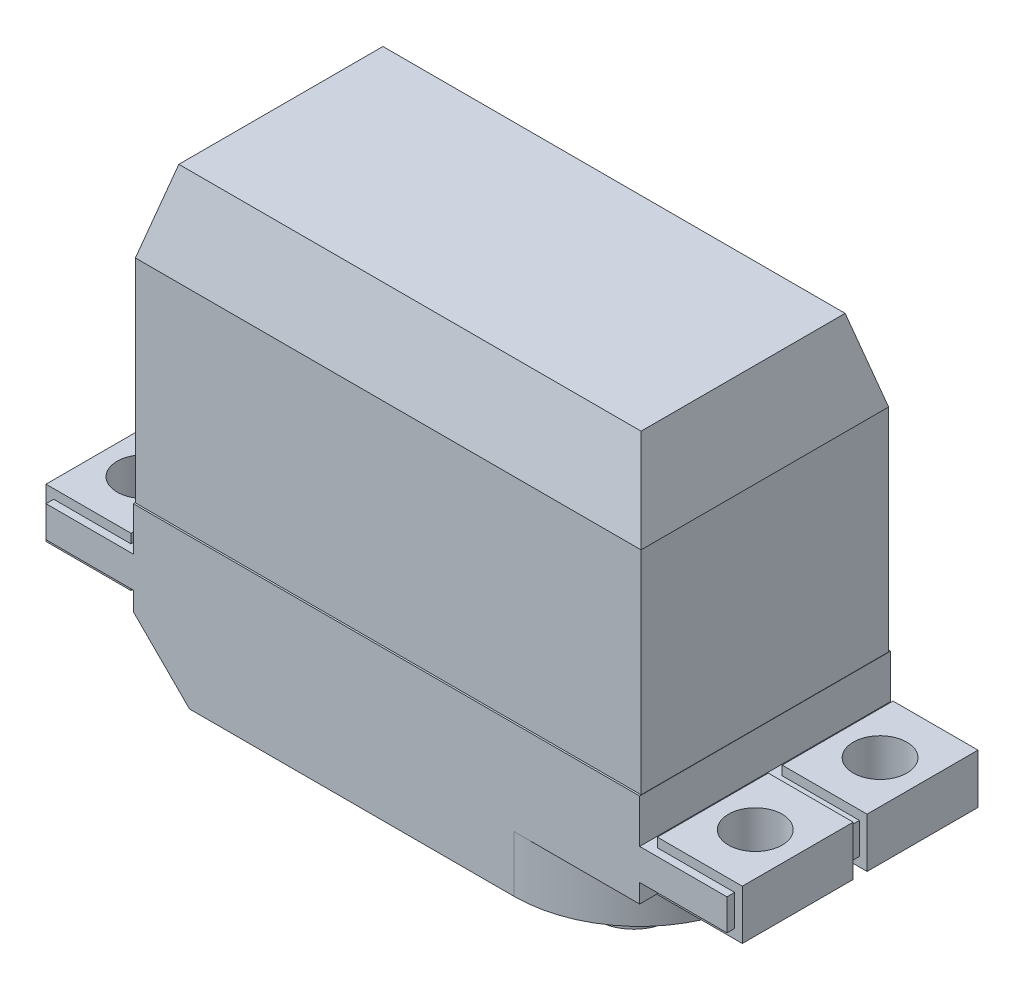
SolidWorks part; units mm, degrees
ref_plane "Piano frontale" through (0, 0, 0) normal (0, 0, 1) x (1, 0, 0)
ref_plane "Piano superiore" through (0, 0, 0) normal (0, 1, 0) x (1, 0, 0)
ref_plane "Piano destro" through (0, 0, 0) normal (1, 0, 0) x (0, 0, -1)
sketch "Schizzo1" plane through (0, 0, 0) normal (0, 1, 0) x (1, 0, 0)
  line L1 (-20.265, -9.92) -> (20.265, -9.92)
  line L2 (-20.265, -9.92) -> (-20.265, 9.92)
  line L3 (-20.265, 9.92) -> (20.265, 9.92)
  line L4 (20.265, -9.92) -> (20.265, 9.92)
  line L5 (-20.265, -9.92) -> (20.265, 9.92) construction
  line L6 (-20.265, 9.92) -> (20.265, -9.92) construction
  point P0 (0, 0)
  dimension "D1" = 40.53
  dimension "D2" = 19.84
extrude "Estrusione-Estrusione1" add sketch "Schizzo1" along normal blind 17
sketch "Schizzo2" plane through (0, 17, 0) normal (0, 1, 0) x (1, 0, 0)
  line L1 (-20.265, -9.92) -> (20.265, -9.92)
  line L2 (-20.265, -9.92) -> (-20.265, 9.92)
  line L3 (-20.265, 9.92) -> (20.265, 9.92)
  line L4 (20.265, -9.92) -> (20.265, 9.92)
  line L5 (-20.265, -9.92) -> (20.265, 9.92) construction
  line L6 (-20.265, 9.92) -> (20.265, -9.92) construction
  point P0 (0, 0)
extrude "Estrusione-Estrusione2" add sketch "Schizzo2" along normal blind 6.5 draft 15
sketch "Schizzo3" plane through (0, 0, 0) normal (0, -1, 0) x (-1, 0, 0)
  line L1 (20.29, 10.06) -> (-20.29, 10.06)
  line L2 (20.29, 10.06) -> (20.29, -10.06)
  line L3 (20.29, -10.06) -> (-20.29, -10.06)
  line L4 (-20.29, 10.06) -> (-20.29, -10.06)
  line L5 (20.29, 10.06) -> (-20.29, -10.06) construction
  line L6 (20.29, -10.06) -> (-20.29, 10.06) construction
  point P0 (0, 0)
  dimension "D1" = 20.12
  dimension "D2" = 40.58
extrude "Estrusione-Estrusione3" add sketch "Schizzo3" along normal blind 7.5
sketch "Schizzo5" plane through (0, -7.5, 0) normal (0, -1, 0) x (1, 0, 0)
  line L0 (20.29, 10.06) -> (-20.29, 10.06) construction
  line L1 (-20.29, -10.06) -> (10.23, -10.06)
  line L2 (-20.29, -10.06) -> (-20.29, 10.06)
  line L3 (-20.29, 10.06) -> (10.23, 10.06)
  line L4 (10.23, -10.06) -> (10.23, 10.06)
  line L5 (20.29, -10.06) -> (20.29, 10.06) construction
  arc A0 (10.23, -10.06) -> (10.23, 10.06) centre (10.23, 0) ccw
  line M2 (20.29, 10.06) -> (-20.29, 10.06)
  line M3 (-20.29, 10.06) -> (-20.29, -10.06)
  line M4 (-20.29, -10.06) -> (20.29, -10.06)
extrude "Estrusione-Estrusione4" add sketch "Schizzo5" along normal blind 4.5 contours L4 A0 | L4 M4 M2 M3
sketch "Schizzo6" plane through (0, -12, 0) normal (0, -1, 0) x (1, 0, 0)
  line L0 (20.29, 0) -> (20.29, 10.06) construction
  circle A0 centre (9.755, 0) radius 6.035
  point P2 (15.79, 0)
  dimension "D1" = 12.07
  dimension "D2" = 4.5
extrude "Estrusione-Estrusione5" add sketch "Schizzo6" along normal blind 1.5
sketch "Schizzo7" plane through (0, -13.5, 0) normal (0, -1, 0) x (1, 0, 0)
  circle A0 centre (9.755, 0) radius 2.9
  circle A1 centre (9.755, 0) radius 6.035 construction
  dimension "D1" = 5.8
extrude "Estrusione-Estrusione6" add sketch "Schizzo7" along normal blind 4
chamfer "Smusso1" distance 4.5 angle 45 1 edges at (-20.29, -12, 0)
ref_plane "Piano1" through (0, -3.5, 0) normal (0, 1, 0) x (1, 0, 0)
sketch "Schizzo8" plane through (0, -3.5, 0) normal (0, 1, 0) x (1, 0, 0)
  line L0 (-24.5, 5) -> (-24.5, -5) construction
  line L1 (-20.29, -10.06) -> (-27.29, -10.06)
  line L2 (-20.29, -10.06) -> (-20.29, 10.06)
  line L3 (-20.29, 10.06) -> (-27.29, 10.06)
  line L4 (-27.29, -10.06) -> (-27.29, 10.06)
  line L5 (-24.5, 0) -> (-20.29, 0) construction
  line L6 (0, 0) -> (0, 10.06) construction
  line L7 (-15.79, 10.06) -> (10.23, 10.06) construction
  line L8 (24.5, 0) -> (20.29, 0) construction
  line L9 (24.5, 5) -> (24.5, -5) construction
  line L10 (27.29, -10.06) -> (27.29, 10.06)
  line L11 (20.29, 10.06) -> (27.29, 10.06)
  line L12 (20.29, -10.06) -> (20.29, 10.06)
  line L13 (20.29, -10.06) -> (27.29, -10.06)
  line L14 (-27.29, -6.2) -> (-26.284, -6.2)
  line L15 (-27.29, -3.8) -> (-26.284, -3.8)
  line L16 (-24.5, -5) -> (-27.29, -5) construction
  line L17 (-27.29, 3.8) -> (-26.284, 3.8)
  line L18 (-26.284, 6.2) -> (-27.29, 6.2)
  line L19 (-24.5, 5) -> (-32.1444, 5) construction
  line L20 (27.29, -3.8) -> (26.284, -3.8)
  line L21 (27.29, -6.2) -> (26.284, -6.2)
  line L22 (27.29, 3.8) -> (26.284, 3.8)
  line L23 (26.284, 6.2) -> (27.29, 6.2)
  circle A0 centre (-24.5, -5) radius 2.15
  circle A1 centre (-24.5, 5) radius 2.15
  circle A2 centre (24.5, 5) radius 2.15
  circle A3 centre (24.5, -5) radius 2.15
  point P12 (-20.29, 0)
  dimension "D2" = 4.3
  dimension "D1" = 7
  dimension "D3" = 10
  dimension "D4" = 49
  dimension "D5" = 2.4
  dimension "D6" = 2.4
extrude "Estrusione-Estrusione7" add sketch "Schizzo8" against normal blind 2.5 contours A1 L17 L4 L15 A0 L14 L1 L2 L3 L18 | L21 A3 L20 L10 L22 A2 L23 L11 L12 L13
ref_plane "Piano2" through (0, -4.75, 0) normal (0, -1, 0) x (-1, 0, 0)
sketch "Schizzo11" plane through (0, -4.75, 0) normal (0, -1, 0) x (-1, 0, 0)
  line L1 (21.095, 0.555) -> (27.905, 0.555)
  line L2 (21.095, 0.555) -> (21.095, 9.445)
  line L3 (21.095, 9.445) -> (27.905, 9.445)
  line L4 (27.905, 0.555) -> (27.905, 9.445)
  line L5 (21.095, 0.555) -> (27.905, 9.445) construction
  line L6 (21.095, 9.445) -> (27.905, 0.555) construction
  line L7 (27.905, -9.445) -> (21.095, -9.445)
  line L8 (27.905, -9.445) -> (27.905, -0.555)
  line L9 (27.905, -0.555) -> (21.095, -0.555)
  line L10 (21.095, -9.445) -> (21.095, -0.555)
  line L11 (27.905, -9.445) -> (21.095, -0.555) construction
  line L12 (27.905, -0.555) -> (21.095, -9.445) construction
  circle A0 centre (24.5, 5) radius 2.15
  arc A1 (26.284, 6.2) -> (26.284, 3.8) centre (24.5, 5) ccw construction
  circle A2 centre (24.5, -5) radius 2.15
  arc A3 (26.284, -3.8) -> (26.284, -6.2) centre (24.5, -5) ccw construction
  point P0 (24.5, 5)
  dimension "D1" = 8.89
  dimension "D2" = 6.81
extrude "Estrusione-Estrusione8" add sketch "Schizzo11" along normal mid plane 3.98
mirror "Specchia1" about plane through (0, 0, 0) normal (1, 0, 0) of "Estrusione-Estrusione8"
